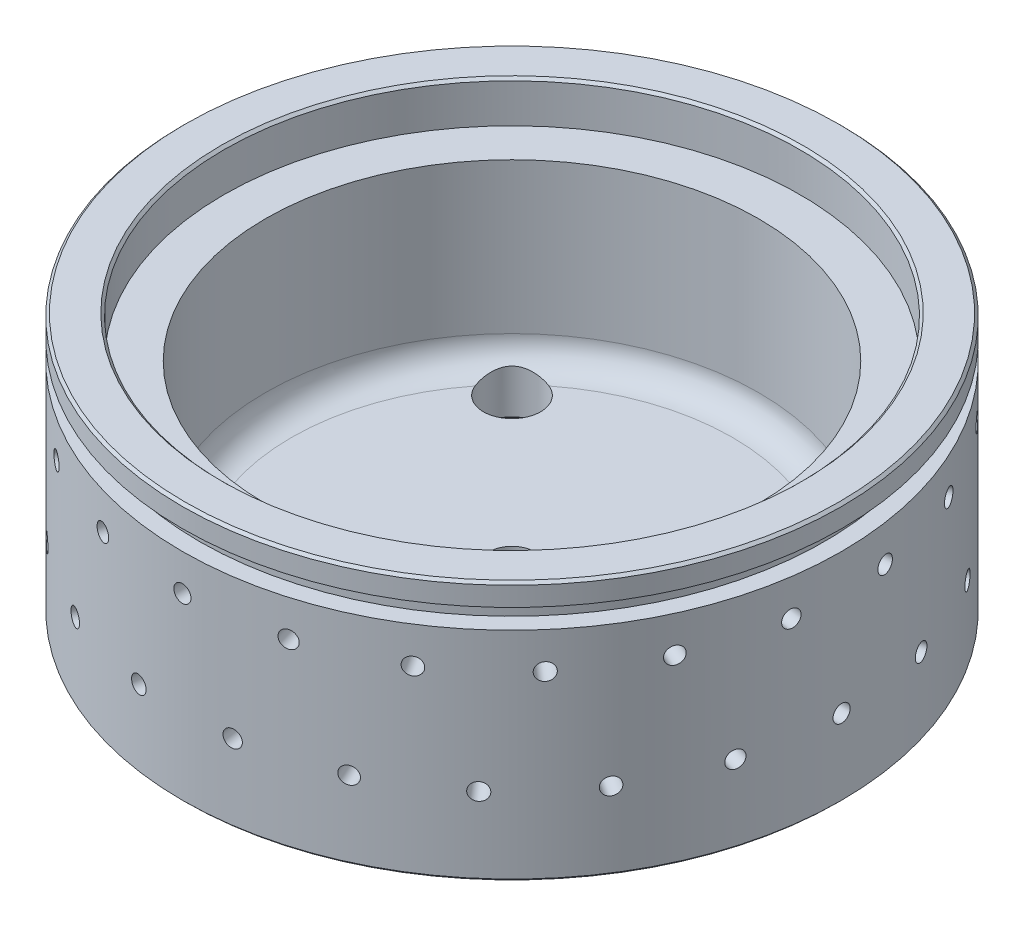
SolidWorks part; units mm, degrees
material "3.1325 (EN-AW 2017A)"
ref_plane "Front Plane" through (0, 0, 0) normal (0, 0, 1) x (1, 0, 0)
ref_plane "Top Plane" through (0, 0, 0) normal (0, 1, 0) x (1, 0, 0)
ref_plane "Right Plane" through (0, 0, 0) normal (1, 0, 0) x (0, 0, -1)
sketch "Sketch1" plane through (0, 0, 0) normal (0, 0, 1) x (1, 0, 0)
  line L0 (0, -55.1447) -> (0, 55.1447) construction
  line L1 (0, 0) -> (63.5, 0)
  line L2 (63.5, 0) -> (63.5, 50)
  line L3 (63.5, 50) -> (55.5, 50)
  line L4 (55.5, 50) -> (55.5, 42)
  line L5 (55.5, 42) -> (47.5, 42)
  line L6 (47.5, 42) -> (47.5, 8)
  line L7 (47.5, 8) -> (0, 8)
  line L8 (0, 8) -> (0, 0)
  point P4 (0, 0)
  dimension "D1" = 127
  dimension "D2" = 50
  dimension "D3" = 95
  dimension "D4" = 111
  dimension "D5" = 8
  dimension "D6" = 34
revolve "Revolve1" add sketch "Sketch1" angle 360 about L0
sketch "Sketch2" plane through (0, 0, 0) normal (0, 0, 1) x (1, 0, 0)
  line L0 (0, -69.8687) -> (0, 69.8687) construction
  line L2 (-63.5, 45.8) -> (-60.2, 45.8)
  line L3 (-63.5, 50) -> (-63.5, 0) construction
  line L4 (-60.2, 45.8) -> (-60.2, 42)
  line L5 (-60.2, 42) -> (-63.5, 42)
  line L6 (-63.5, 42) -> (-63.5, 45.8)
  line L7 (63.5, 50) -> (-63.5, 50) construction
  point P4 (0, 0)
  dimension "D1" = 3.3
  dimension "D2" = 4.2
  dimension "D3" = 3.8
revolve "Cut-Revolve1" cut sketch "Sketch2" angle 360 about L0
fillet "Fillet1" radius 5 1 edges at (47.5, 8, 0)
chamfer "Chamfer1" distance 0.5 angle 45 3 edges at (63.5, 0, 0) (63.5, 50, 0) (55.5, 50, 0)
ref_plane "Plane1" through (-63.5, 0, 0) normal (-1, 0, 0) x (0, 0, 1)
hole_wizard "M4x0.7 Tapped Hole1" positions "Sketch3" profile "Sketch4" tap size "M4x0.7" standard "ANSI Metric"
sketch "Sketch3" plane through (-63.5, 0, 0) normal (-1, 0, 0) x (0, 0, 1)
  line L0 (-63, 0) -> (63, 0) construction
  point P0 (0, 15)
  dimension "D1" = 15
sketch "Sketch4" plane through (-63.5, 15, 0) normal (0, 1, 0) x (0, 0, 1)
  line L0 (0, 0) -> (0, 10)
  line L1 (0, 10) -> (1.65, 9.0086)
  line L2 (1.65, 9.0086) -> (1.65, 0)
  line L5 (1.65, 0) -> (0, 0)
  line L10 (0, 10) -> (-1.65, 9.0086) construction
  line L11 (0, -6.35) -> (0, 107.95) construction
  dimension "Tap Drill Dia." = 3.3
  dimension "Tap Drill Depth" = 10
  dimension "Drill Angle" = 118
cosmetic thread "Hole Thread1" parameters "D1"=6, "D2"=4
pattern_circular "CirPattern1" count 22 over 360 about axis through (0, -55.1447, 0) along (0, -1, 0) of "M4x0.7 Tapped Hole1"
cosmetic thread "Hole Thread2" parameters "D1"=6, "D2"=4
cosmetic thread "Hole Thread3" parameters "D1"=6, "D2"=4
cosmetic thread "Hole Thread4" parameters "D1"=6, "D2"=4
cosmetic thread "Hole Thread5" parameters "D1"=6, "D2"=4
cosmetic thread "Hole Thread6" parameters "D1"=6, "D2"=4
cosmetic thread "Hole Thread7" parameters "D1"=6, "D2"=4
cosmetic thread "Hole Thread8" parameters "D1"=6, "D2"=4
cosmetic thread "Hole Thread9" parameters "D1"=6, "D2"=4
cosmetic thread "Hole Thread10" parameters "D1"=6, "D2"=4
cosmetic thread "Hole Thread11" parameters "D1"=6, "D2"=4
cosmetic thread "Hole Thread12" parameters "D1"=6, "D2"=4
cosmetic thread "Hole Thread13" parameters "D1"=6, "D2"=4
cosmetic thread "Hole Thread14" parameters "D1"=6, "D2"=4
cosmetic thread "Hole Thread15" parameters "D1"=6, "D2"=4
cosmetic thread "Hole Thread16" parameters "D1"=6, "D2"=4
cosmetic thread "Hole Thread17" parameters "D1"=6, "D2"=4
cosmetic thread "Hole Thread18" parameters "D1"=6, "D2"=4
cosmetic thread "Hole Thread19" parameters "D1"=6, "D2"=4
cosmetic thread "Hole Thread20" parameters "D1"=6, "D2"=4
cosmetic thread "Hole Thread21" parameters "D1"=6, "D2"=4
cosmetic thread "Hole Thread22" parameters "D1"=6, "D2"=4
ref_plane "Plane2" through (-62.8537, 0, -9.037) normal (-0.9898, 0, -0.1423) x (0, -1, 0)
hole_wizard "M4x0.7 Tapped Hole2" positions "Sketch5" profile "Sketch6" tap size "M4x0.7" standard "ANSI Metric"
sketch "Sketch5" plane through (-62.8537, 0, -9.037) normal (-0.9898, 0, -0.1423) x (0, -1, 0)
  line L0 (0, -63) -> (0, 63) construction
  point P0 (-35, 0)
  dimension "D1" = 35
sketch "Sketch6" plane through (-62.8537, 35, -9.037) normal (0, 1, 0) x (-0.1423, 0, 0.9898)
  line L0 (0, 0) -> (0, 10)
  line L1 (0, 10) -> (1.65, 9.0086)
  line L2 (1.65, 9.0086) -> (1.65, 0)
  line L5 (1.65, 0) -> (0, 0)
  line L10 (0, 10) -> (-1.65, 9.0086) construction
  line L11 (0, -6.35) -> (0, 107.95) construction
  dimension "Tap Drill Dia." = 3.3
  dimension "Tap Drill Depth" = 10
  dimension "Drill Angle" = 118
cosmetic thread "Hole Thread23" parameters "D1"=6, "D2"=4
pattern_circular "CirPattern2" count 22 over 360 about axis through (0, -55.1447, 0) along (0, -1, 0) of "M4x0.7 Tapped Hole2"
cosmetic thread "Hole Thread24" parameters "D1"=6, "D2"=4
cosmetic thread "Hole Thread25" parameters "D1"=6, "D2"=4
cosmetic thread "Hole Thread26" parameters "D1"=6, "D2"=4
cosmetic thread "Hole Thread27" parameters "D1"=6, "D2"=4
cosmetic thread "Hole Thread28" parameters "D1"=6, "D2"=4
cosmetic thread "Hole Thread29" parameters "D1"=6, "D2"=4
cosmetic thread "Hole Thread30" parameters "D1"=6, "D2"=4
cosmetic thread "Hole Thread31" parameters "D1"=6, "D2"=4
cosmetic thread "Hole Thread32" parameters "D1"=6, "D2"=4
cosmetic thread "Hole Thread33" parameters "D1"=6, "D2"=4
cosmetic thread "Hole Thread34" parameters "D1"=6, "D2"=4
cosmetic thread "Hole Thread35" parameters "D1"=6, "D2"=4
cosmetic thread "Hole Thread36" parameters "D1"=6, "D2"=4
cosmetic thread "Hole Thread37" parameters "D1"=6, "D2"=4
cosmetic thread "Hole Thread38" parameters "D1"=6, "D2"=4
cosmetic thread "Hole Thread39" parameters "D1"=6, "D2"=4
cosmetic thread "Hole Thread40" parameters "D1"=6, "D2"=4
cosmetic thread "Hole Thread41" parameters "D1"=6, "D2"=4
cosmetic thread "Hole Thread42" parameters "D1"=6, "D2"=4
cosmetic thread "Hole Thread43" parameters "D1"=6, "D2"=4
cosmetic thread "Hole Thread44" parameters "D1"=6, "D2"=4
hole_wizard "G1/8 Tapped Hole1" positions "Sketch7" profile "Sketch8" tap size "G1/8" standard "GB" end condition up to next
sketch "Sketch7" plane through (0, 0, 0) normal (0, -1, 0) x (-1, 0, 0)
  point P0 (0, 0)
sketch "Sketch8" plane through (0, 0, 0) normal (1, 0, 0) x (0, 0, -1)
  line L0 (0, 0) -> (0, 8)
  line L1 (0, 8) -> (4.4, 8)
  line L2 (4.4, 8) -> (4.4, 0)
  line L5 (4.4, 0) -> (0, 0)
  line L11 (0, -6.35) -> (0, 107.95) construction
  dimension "Thru Tap Drill Dia." = 8.8
  dimension "Thru Tap Drill Depth" = 8
cosmetic thread "Hole Thread45" parameters "D2"=9.728
hole_wizard "G1/4 Tapped Hole1" positions "Sketch9" profile "Sketch10" tap size "G1/4" standard "GB" end condition up to next
sketch "Sketch9" plane through (0, 0, 0) normal (0, -1, 0) x (-1, 0, 0)
  point P0 (-30, 0)
  dimension "D1" = 30
sketch "Sketch10" plane through (30, 0, 0) normal (1, 0, 0) x (0, 0, -1)
  line L0 (0, 0) -> (0, 8)
  line L1 (0, 8) -> (5.9, 8)
  line L2 (5.9, 8) -> (5.9, 0)
  line L5 (5.9, 0) -> (0, 0)
  line L11 (0, -6.35) -> (0, 107.95) construction
  dimension "Thru Tap Drill Dia." = 11.8
  dimension "Thru Tap Drill Depth" = 8
cosmetic thread "Hole Thread46" parameters "D2"=13.157
hole_wizard "M12x1.0 Tapped Hole1" positions "Sketch11" profile "Sketch12" tap size "M12x1.0" standard "DIN"
sketch "Sketch11" plane through (0, 0, 0) normal (0, -1, 0) x (-1, 0, 0)
  line L0 (0, 0) -> (28.2843, 28.2843) construction
  line L3 (0, 0) -> (0, 38.3783) construction
  point P0 (28.2843, 28.2843)
  dimension "D1" = 40
  dimension "D2" = 45
sketch "Sketch12" plane through (-28.2843, 0, -28.2843) normal (1, 0, 0) x (0, 0, -1)
  line L0 (0, 0) -> (0, 27)
  line L1 (0, 27) -> (5.5, 23.6953)
  line L2 (5.5, 23.6953) -> (5.5, 0.525)
  line L3 (5.5, 0.525) -> (6.025, 0)
  line L5 (6.025, 0) -> (0, 0)
  line L6 (-5.5, 0.525) -> (-6.025, 0) construction
  line L10 (0, 27) -> (-5.5, 23.6953) construction
  line L11 (0, -6.35) -> (0, 107.95) construction
  dimension "Tap Drill Dia." = 11
  dimension "Tap Drill Depth" = 27
  dimension "Near C'Sink Dia." = 12.05
  dimension "Near C'Sink Angle" = 90
  dimension "Drill Angle" = 118
cosmetic thread "Hole Thread47" parameters "D1"=24, "D2"=12
hole_wizard "1/8-27 NPSM Tapped Hole1" positions "Sketch13" profile "Sketch14" tap size "1/8-27 NPSM" standard "ANSI Inch"
sketch "Sketch13" plane through (0, 0, 0) normal (0, -1, 0) x (-1, 0, 0)
  line L0 (0, 0) -> (-80.7416, 0) construction
  line L3 (0, 0) -> (-15, 25.9808) construction
  point P0 (-15, 25.9808)
  dimension "D1" = 60
  dimension "D2" = 30
sketch "Sketch14" plane through (15, 0, -25.9808) normal (1, 0, 0) x (0, 0, -1)
  line L0 (0, 0) -> (0, 5)
  line L1 (0, 5) -> (4.7625, 5)
  line L2 (4.7625, 5) -> (4.7625, 0.9144)
  line L3 (4.7625, 0.9144) -> (5.6769, 0)
  line L5 (5.6769, 0) -> (0, 0)
  line L6 (-4.7625, 0.9144) -> (-5.6769, 0) construction
  line L10 (0, 5) -> (-4.7625, 5) construction
  line L11 (0, -6.35) -> (0, 107.95) construction
  dimension "Tap Drill Dia." = 9.525
  dimension "Tap Drill Depth" = 5
  dimension "Near C'Sink Dia." = 11.3538
  dimension "Near C'Sink Angle" = 90
  dimension "Drill Angle" = 180
cosmetic thread "Hole Thread48" parameters "D1"=5, "D2"=10.0838
hole_wizard "Ø3.0 mm Dowel Holes1" positions "Sketch15" profile "Sketch16" hole size "Ø3.0" standard "ANSI Metric"
sketch "Sketch15" plane through (0, 5, 0) normal (0, -1, 0) x (-1, 0, 0)
  point P0 (-15, 25.9808)
sketch "Sketch16" plane through (15, 5, -25.9808) normal (1, 0, 0) x (0, 0, -1)
  line L0 (0, 0) -> (0, 45)
  line L1 (0, 45) -> (1.5, 45)
  line L2 (1.5, 45) -> (1.5, 0.025)
  line L3 (1.5, 0.025) -> (1.525, 0)
  line L5 (1.525, 0) -> (0, 0)
  line L6 (-1.5, 0.025) -> (-1.525, 0) construction
  line L11 (0, -6.35) -> (0, 107.95) construction
  dimension "Thru Hole Dia." = 3
  dimension "Thru Hole Depth" = 45
  dimension "Near C'Sink Dia." = 3.05
  dimension "Near C'Sink Angle" = 90
